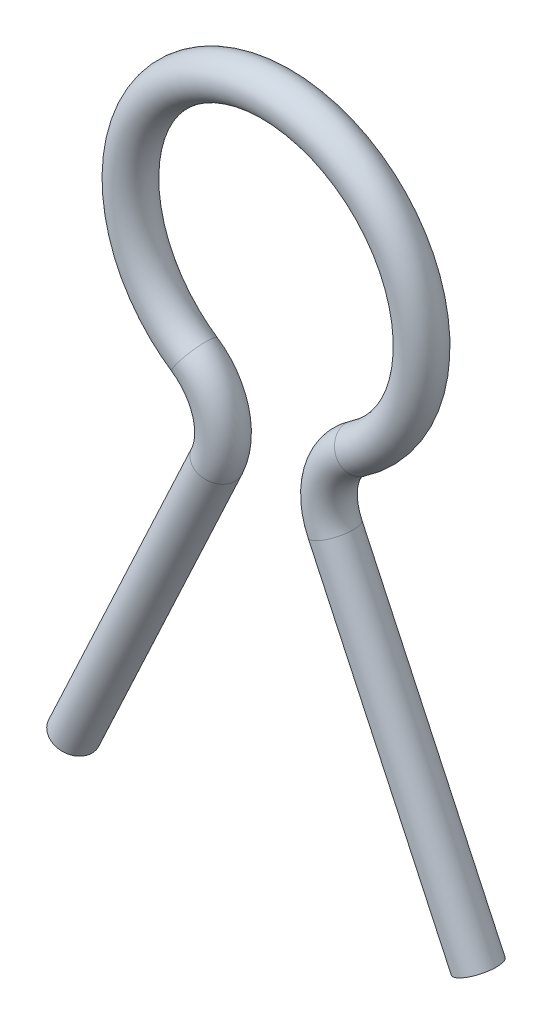
SolidWorks part; units mm, degrees
material "Brass"
ref_plane "Front Plane" through (0, 0, 0) normal (0, 0, 1) x (1, 0, 0)
ref_plane "Top Plane" through (0, 0, 0) normal (0, 1, 0) x (1, 0, 0)
ref_plane "Right Plane" through (0, 0, 0) normal (1, 0, 0) x (0, 0, -1)
sketch "Sketch1" plane through (0, 0, 0) normal (0, 0, 1) x (1, 0, 0)
  line L0 (0, 0) -> (-5.6207, 12.0537)
  line L1 (-10.2543, 12.0537) -> (-15.875, 0)
  line L2 (-7.9375, 19.969) -> (-7.9375, 2.5532) construction
  arc A0 (-4.7399, 15.2323) -> (-11.1351, 15.2323) centre (-7.9375, 19.969) ccw
  arc A1 (-11.1351, 15.2323) -> (-10.2543, 12.0537) centre (-12.5563, 13.1271) cw
  arc A2 (-4.7399, 15.2323) -> (-5.6207, 12.0537) centre (-3.3187, 13.1271) ccw
  point P12 (-9.1659, 14.3876)
  point P15 (-6.7091, 14.3876)
  dimension "D1" = 5.715
  dimension "D8" = 2.54
  dimension "D2" = 15.875
  dimension "D3" = 15.875
  dimension "D4" = 25
  dimension "D5" = 25
  dimension "D6" = 7.9375
  dimension "D7" = 25.684
ref_plane "Plane1" through (0, 0, 0) normal (-0.4226, 0.9063, 0) x (0.9063, 0.4226, 0)
sketch "Sketch3" plane through (0, 0, 0) normal (-0.4226, 0.9063, 0) x (0.9063, 0.4226, 0)
  circle A0 centre (0, 0) radius 0.7874
  dimension "D1" = 1.5748
sweep "Sweep1" add profiles "Sketch3" path "Sketch1"
